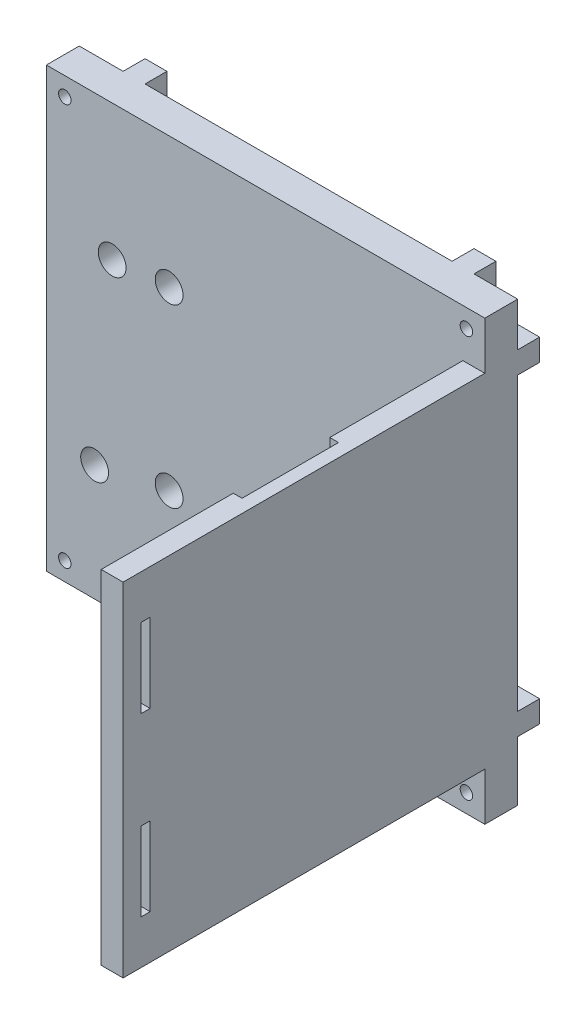
SolidWorks part; units mm, degrees
material "ABS"
ref_plane "Plan de face" through (0, 0, 0) normal (0, 0, 1) x (1, 0, 0)
ref_plane "Plan de dessus" through (0, 0, 0) normal (0, 1, 0) x (1, 0, 0)
ref_plane "Plan de droite" through (0, 0, 0) normal (1, 0, 0) x (0, 0, -1)
sketch "Esquisse3" plane through (0, 0, 0) normal (0, 0, 1) x (1, 0, 0)
  line L1 (-50, 50) -> (50, 50)
  line L2 (-50, 50) -> (-50, -50)
  line L3 (-50, -50) -> (50, -50)
  line L4 (50, 50) -> (50, -50)
  line L5 (-50, 50) -> (50, -50) construction
  line L6 (-50, -50) -> (50, 50) construction
  point P0 (0, 0)
  dimension "D1" = 100
  dimension "D2" = 100
extrude "Boss.-Extru.1" add sketch "Esquisse3" against normal blind 7.5
sketch "Esquisse4" plane through (0, 0, -7.5) normal (0, 0, -1) x (-1, 0, 0)
  line L0 (-50, 50) -> (-40.0349, 50) construction
  line L1 (-50, 50) -> (50, 50) construction
  line L2 (50, 50) -> (40, 50) construction
  line L3 (-40.0349, 50) -> (-35.0349, 50)
  line L4 (-40.0349, 50) -> (-40.0349, 45)
  line L5 (-40.0349, 45) -> (-35.0349, 45)
  line L6 (-35.0349, 50) -> (-35.0349, 45)
  line L7 (50, 50) -> (50, 40) construction
  line L8 (40, 50) -> (35, 50)
  line L9 (40, 50) -> (40, 45)
  line L10 (40, 45) -> (35, 45)
  line L11 (35, 50) -> (35, 45)
  line L12 (50, 50) -> (50, -50) construction
  line L13 (50, -50) -> (50, -40) construction
  line L14 (50, 40) -> (45, 40)
  line L15 (50, 40) -> (50, 35)
  line L16 (50, 35) -> (45, 35)
  line L17 (45, 40) -> (45, 35)
  line L18 (50, -50) -> (40, -50) construction
  line L19 (50, -40) -> (45, -40)
  line L20 (50, -40) -> (50, -35)
  line L21 (50, -35) -> (45, -35)
  line L22 (45, -40) -> (45, -35)
  line L23 (50, -50) -> (-50, -50) construction
  line L24 (-50, -50) -> (-40.0349, -50) construction
  line L25 (40, -50) -> (35, -50)
  line L26 (40, -50) -> (40, -45)
  line L27 (40, -45) -> (35, -45)
  line L28 (35, -50) -> (35, -45)
  line L29 (-50, -50) -> (-50, -36.4288) construction
  line L30 (-50, -50) -> (-50, 50) construction
  line L31 (-50, 50) -> (-50, 40) construction
  line L32 (-40.0349, -50) -> (-35.0349, -50)
  line L33 (-40.0349, -50) -> (-40.0349, -45)
  line L34 (-40.0349, -45) -> (-35.0349, -45)
  line L35 (-35.0349, -50) -> (-35.0349, -45)
  line L36 (-50, -36.4288) -> (-45, -36.4288)
  line L37 (-50, -36.4288) -> (-50, -31.4288)
  line L38 (-50, -31.4288) -> (-45, -31.4288)
  line L39 (-45, -36.4288) -> (-45, -31.4288)
  line L41 (-50, 40) -> (-45, 40)
  line L42 (-50, 40) -> (-50, 35)
  line L43 (-50, 35) -> (-45, 35)
  line L44 (-45, 40) -> (-45, 35)
  dimension "D1" = 5
  dimension "D2" = 5
  dimension "D3" = 10
  dimension "D4" = 5
  dimension "D5" = 5
  dimension "D6" = 10
  dimension "D7" = 5
  dimension "D8" = 5
  dimension "D9" = 10
  dimension "D10" = 5
  dimension "D11" = 5
  dimension "D12" = 10
  dimension "D13" = 5
  dimension "D14" = 5
  dimension "D15" = 5
  dimension "D16" = 5
  dimension "D17" = 5
  dimension "D18" = 5
  dimension "D19" = 5
  dimension "D20" = 5
extrude "Boss.-Extru.2" add sketch "Esquisse4" along normal blind 5
sketch "Esquisse5" plane through (0, 0, 0) normal (0, 0, 1) x (1, 0, 0)
  line L0 (-50, -50) -> (-35, -50) construction
  line L1 (-50, -50) -> (50, -50) construction
  line L7 (50, 50) -> (-50, 50) construction
  line L11 (-50, 50) -> (-50, -50) construction
  line L12 (-50, 45.8) -> (-45.8, 45.8) construction
  line L13 (-50, -50) -> (-45.8, -50) construction
  line L14 (-45.8, -50) -> (-45.8, -45.8) construction
  line L15 (50, -50) -> (50, -45.8) construction
  line L16 (50, -50) -> (50, 50) construction
  line L17 (50, -45.8) -> (45.8, -45.8) construction
  line L18 (50, 50) -> (50, 45.8) construction
  line L19 (50, 45.8) -> (45.8, 45.8) construction
  circle A0 centre (-35, 19) radius 3.175
  circle A5 centre (-39, -23.5) radius 3.175
  circle A6 centre (-45.8, 45.8) radius 1.42
  circle A7 centre (-45.8, -45.8) radius 1.42
  circle A8 centre (45.8, -45.8) radius 1.42
  circle A9 centre (45.8, 45.8) radius 1.42
  circle A10 centre (-22, 20.1) radius 3.175
  circle A11 centre (-22, -20.1) radius 3.175
  dimension "D6" = 6.35
  dimension "D9" = 2.84
  dimension "D12" = 2.84
  dimension "D13" = 2.84
  dimension "D14" = 2.84
  dimension "D3" = 31
  dimension "D4" = 13
  dimension "D19" = 29.9
  dimension "D2" = 15
  dimension "D5" = 28
  dimension "D7" = 4.2
  dimension "D8" = 4.2
  dimension "D10" = 4.2
  dimension "D11" = 4.2
  dimension "D15" = 4.2
  dimension "D16" = 4.2
  dimension "D17" = 4.2
  dimension "D18" = 4.2
  dimension "D20" = 17
  dimension "D21" = 26.5
  dimension "D22" = 29.9
extrude "Enlèv. mat.-Extru.1" cut sketch "Esquisse5" against normal blind 10
sketch "Esquisse6" plane through (0, 0, 0) normal (0, 0, 1) x (1, 0, 0)
  line L0 (50, 0) -> (50, 39.1)
  line L1 (50, -50) -> (50, 50) construction
  line L2 (50, 0) -> (50, -39.1)
  line L3 (50, 39.1) -> (45, 39.1)
  line L4 (45, 39.1) -> (45, -39.1)
  line L5 (45, -39.1) -> (50, -39.1)
  dimension "D1" = 39.1
  dimension "D2" = 39.1
  dimension "D3" = 5
extrude "Boss.-Extru.3" add sketch "Esquisse6" along normal blind 82.5
sketch "Esquisse7" plane through (45, 0, 0) normal (-1, 0, 0) x (0, 0, 1)
  line L0 (0, 39.1) -> (41.4, 39.1) construction
  line L1 (82.5, 39.1) -> (0, 39.1) construction
  line L2 (41.4, 39.1) -> (41.4, 20.1) construction
  line L3 (41.4, 20.1) -> (41.4, -20.1) construction
  line L4 (22.4, 39.1) -> (30.3591, 39.1) construction
  line L5 (22.4, 39.1) -> (60.4, 39.1)
  line L6 (22.4, 39.1) -> (22.4, 1.1)
  line L7 (22.4, 1.1) -> (60.4, 1.1)
  line L8 (60.4, 39.1) -> (60.4, 1.1)
  line L9 (22.4, 39.1) -> (60.4, 1.1) construction
  line L10 (22.4, 1.1) -> (60.4, 39.1) construction
  line L11 (22.4, -1.1) -> (60.4, -1.1)
  line L12 (22.4, -1.1) -> (22.4, -39.1)
  line L13 (22.4, -39.1) -> (60.4, -39.1)
  line L14 (60.4, -1.1) -> (60.4, -39.1)
  line L15 (22.4, -1.1) -> (60.4, -39.1) construction
  line L16 (22.4, -39.1) -> (60.4, -1.1) construction
  line L17 (22.4, 39.1) -> (22.4, 31.097) construction
  line L18 (60.4, 39.1) -> (52.3764, 39.1) construction
  line L19 (60.4, 39.1) -> (60.4, 31.097) construction
  line L20 (30.3591, 39.1) -> (30.3591, 31.1409)
  line L21 (30.3591, 31.1409) -> (22.4, 31.097)
  line L22 (30.3591, 39.1) -> (52.3764, 39.1)
  line L23 (52.3764, 39.1) -> (52.3764, 31.0764)
  line L24 (52.3764, 31.0764) -> (60.4, 31.097)
  line L25 (22.4, 1.1) -> (22.4, 9.0722) construction
  line L26 (60.4, 1.1) -> (60.4, 9.0722) construction
  line L27 (22.4, 31.097) -> (22.4, 9.0722)
  line L28 (22.4, 9.0722) -> (30.3722, 9.0722)
  line L29 (30.3722, 9.0722) -> (30.3722, 1.1)
  line L30 (30.3722, 1.1) -> (52.3764, 1.1)
  line L31 (52.3764, 1.1) -> (52.3764, 9.1236)
  line L32 (52.3764, 9.1236) -> (60.4, 9.0722)
  line L33 (60.4, 9.0722) -> (60.4, 31.097)
  line L34 (30.3722, -1.1) -> (52.3764, -1.1)
  line L35 (52.3764, -1.1) -> (52.3764, -9.1236)
  line L36 (52.3764, -9.1236) -> (60.4, -9.1236)
  line L37 (30.3722, -1.1) -> (30.3722, -9.0722)
  line L38 (30.3722, -9.0722) -> (22.4, -9.0722)
  line L39 (22.4, -39.1) -> (22.4, -31.0799) construction
  line L40 (22.4, -9.0722) -> (22.4, -31.0799)
  line L41 (22.4, -31.0799) -> (30.4201, -31.0799)
  line L42 (30.4201, -31.0799) -> (30.4201, -39.1)
  line L43 (30.4201, -39.1) -> (52.3764, -39.1)
  line L44 (52.3764, -39.1) -> (52.3764, -31.0764)
  line L45 (52.3764, -31.0764) -> (60.4, -31.0764)
  line L46 (60.4, -31.0764) -> (60.4, -9.1236)
  dimension "D1" = 41.4
  dimension "D2" = 19
  dimension "D3" = 40.2
  dimension "D4" = 38
  dimension "D5" = 38
  dimension "D6" = 38
  dimension "D7" = 38
extrude "Enlèv. mat.-Extru.2" cut sketch "Esquisse7" against normal blind 2 contours L31 L32 L8 L24 L23 L5 L20 L21 L6 L28 L29 L7 | L44 L45 L14 L36 L35 L11 L37 L38 L12 L41 L42 L13
sketch "Esquisse8" plane through (45, 0, 0) normal (-1, 0, 0) x (0, 0, 1)
  line L0 (60.4, -9.1236) -> (60.4, -11.1236) construction
  line L1 (60.4, -9.1236) -> (60.4, -31.0764) construction
  line L2 (60.4, -11.1236) -> (78.3775, -11.1236)
  line L3 (60.4, -31.0764) -> (60.4, -29.0764) construction
  line L4 (60.4, -9.1236) -> (60.4, -31.0764) construction
  line L5 (60.4, -29.0764) -> (60.4, -11.1236)
  line L6 (60.4, -29.0764) -> (78.3775, -29.0764)
  line L7 (78.3775, -29.0764) -> (78.3775, -11.1236)
  line L8 (60.4, 31.097) -> (60.4, 29.097) construction
  line L9 (60.4, 31.097) -> (60.4, 9.0722) construction
  line L10 (60.4, 9.0722) -> (60.4, 11.0722) construction
  line L16 (60.4, 29.097) -> (78.3775, 29.097)
  line L17 (78.3775, 29.097) -> (78.3775, 11.0722)
  line L18 (78.3775, 11.0722) -> (60.4, 11.0722)
  line L19 (60.4, 11.0722) -> (60.4, 29.097)
  dimension "D1" = 2
  dimension "D2" = 2
  dimension "D3" = 2
  dimension "D4" = 2
extrude "Enlèv. mat.-Extru.3" cut sketch "Esquisse8" against normal blind 2
sketch "Esquisse9" plane through (47, 0, 0) normal (-1, 0, 0) x (0, 0, 1)
  point P15 (76.8334, 26.2856)
sketch "Esquisse10" plane through (47, 0, 0) normal (-1, 0, 0) x (0, 0, 1)
  line L0 (78.3775, 29.097) -> (76.3324, 29.097)
  line L1 (78.3775, 29.097) -> (60.4, 29.097) construction
  line L2 (76.3324, 29.097) -> (76.3324, 11.0722)
  line L3 (60.4, 11.0722) -> (78.3775, 11.0722) construction
  line L4 (76.3324, 11.0722) -> (78.3775, 11.0722)
  line L5 (78.3775, 11.0722) -> (78.3775, 29.097)
  line L6 (78.3775, -11.1236) -> (76.3324, -11.1236)
  line L7 (78.3775, -11.1236) -> (60.4, -11.1236) construction
  line L8 (76.3324, -11.1236) -> (76.3324, -29.0764)
  line L9 (60.4, -29.0764) -> (78.3775, -29.0764) construction
  line L10 (76.3324, -29.0764) -> (78.3775, -29.0764)
  line L11 (78.3775, -29.0764) -> (78.3775, -11.1236)
extrude "Enlèv. mat.-Extru.4" cut sketch "Esquisse10" against normal blind 10
